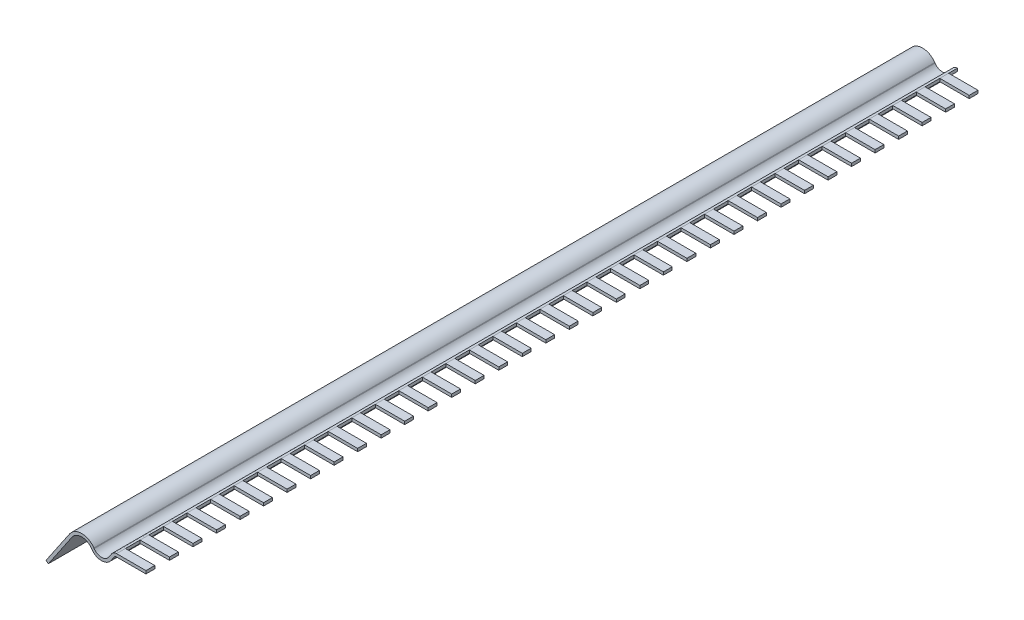
SolidWorks part; units mm, degrees
ref_plane "Front Plane" through (0, 0, 0) normal (0, 0, 1) x (1, 0, 0)
ref_plane "Top Plane" through (0, 0, 0) normal (0, 1, 0) x (1, 0, 0)
ref_plane "Right Plane" through (0, 0, 0) normal (1, 0, 0) x (0, 0, -1)
sketch "Sketch1" plane through (0, 0, 0) normal (0, 0, 1) x (1, 0, 0)
  line L0 (0, 0) -> (-5, 0)
  line L1 (-5.8275, -0.4386) -> (-6.3241, -1.1705)
  line L2 (-8.8067, -1.1705) -> (-8.857, -1.0964)
  line L3 (-12.9945, -1.0964) -> (-17, -7)
  line L4 (-5.53, 0) -> (-10.9257, 0) construction
  line L5 (0, -0.5) -> (-5, -0.5)
  line L6 (-5.4138, -0.7193) -> (-5.9104, -1.4512)
  line L7 (-9.2204, -1.4512) -> (-9.2707, -1.3771)
  line L8 (-12.5808, -1.3771) -> (-16.5862, -7.2807)
  line L9 (-17, -7) -> (-16.5862, -7.2807)
  line L10 (0, 0) -> (0, -0.5)
  arc A0 (-8.8067, -1.1705) -> (-6.3241, -1.1705) centre (-7.5654, -0.3283) ccw
  arc A1 (-8.857, -1.0964) -> (-12.9945, -1.0964) centre (-10.9257, -2.5) ccw
  arc A2 (-5.8275, -0.4386) -> (-5, 0) centre (-5, -1) cw
  arc A3 (-5.4138, -0.7193) -> (-5, -0.5) centre (-5, -1) cw
  arc A4 (-9.2204, -1.4512) -> (-5.9104, -1.4512) centre (-7.5654, -0.3283) ccw
  arc A5 (-9.2707, -1.3771) -> (-12.5808, -1.3771) centre (-10.9257, -2.5) ccw
  point P9 (-7.5654, -3)
  point P12 (-10.9257, 1.9528)
  dimension "D4" = 1.5
  dimension "D5" = 2.5
  dimension "D6" = 1
  dimension "D1" = 3
  dimension "D2" = 7
  dimension "D3" = 5
  dimension "D7" = 17
  dimension "D8" = 0.5
extrude "Boss-Extrude1" add sketch "Sketch1" along normal mid plane 143 contours A5 L8 L9 L3 A1 L2 A0 L1 A2 L0 L10 L5 A3 L6 A4 L7
sketch "Sketch3" plane through (0, 0, 0) normal (0, 1, 0) x (1, 0, 0)
  line L0 (0, -70) -> (-5, -70)
  line L1 (0, -71.5) -> (0, 71.5) construction
  line L2 (-5, -71.5) -> (-5, 71.5) construction
  line L3 (-5, -70) -> (-5, -67.5)
  line L4 (-5, -67.5) -> (0, -67.5)
  line L5 (0, -67.5) -> (0, -70)
  dimension "D1" = 2.5
  dimension "D2" = 1.5
extrude "Cut-Extrude1" cut sketch "Sketch3" against normal through all
pattern_linear "LPattern1" count 36 spacing 4 along (0, 0, -1) of "Cut-Extrude1"
